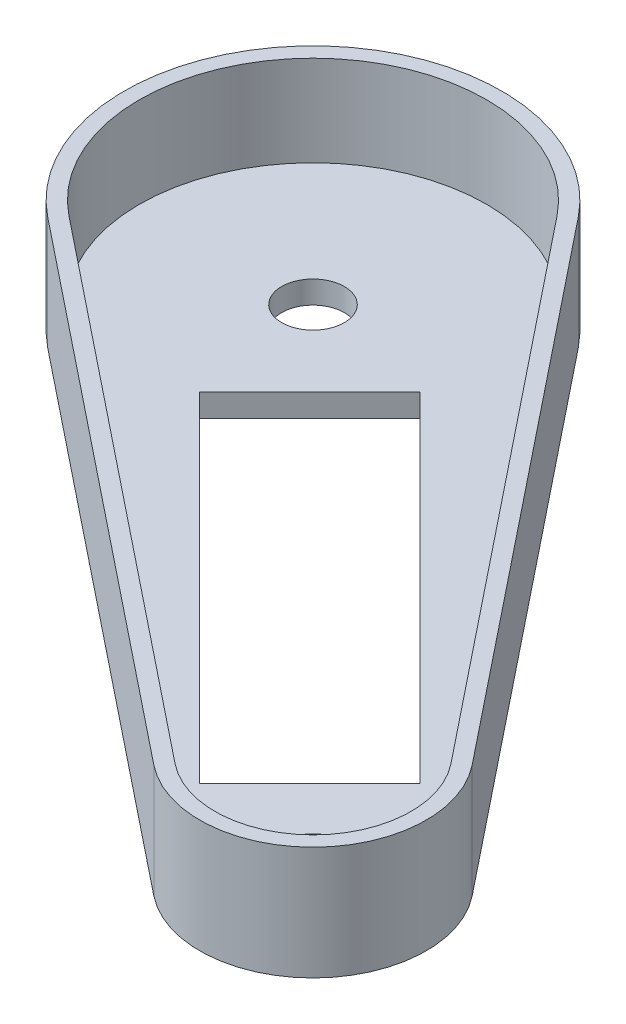
SolidWorks part; units mm, degrees
ref_plane "前视基准面" through (0, 0, 0) normal (0, 0, 1) x (1, 0, 0)
ref_plane "上视基准面" through (0, 0, 0) normal (0, 1, 0) x (1, 0, 0)
ref_plane "右视基准面" through (0, 0, 0) normal (1, 0, 0) x (0, 0, -1)
other "Configuration Table"
sketch "草图1" plane through (0, 0, 0) normal (0, 1, 0) x (1, 0, 0)
  line L0 (-1002.0771, 0) -> (49101.7763, 0) construction
  line L1 (0, -1002.0771) -> (0, 49101.7763) construction
  line L2 (0, 0) -> (63.6396, -63.6396)
  line L3 (19.5324, 15.604) -> (75.359, -54.2772)
  line L4 (-15.604, -19.5324) -> (54.2772, -75.359)
  circle A0 centre (0, 0) radius 4.15
  circle A1 centre (63.6396, -63.6396) radius 4.15
  circle A2 centre (63.6396, -63.6396) radius 15
  circle A3 centre (0, 0) radius 25
  dimension "D2" = 8.3
  dimension "D3" = 8.3
  dimension "D4" = 50
  dimension "D5" = 30
  dimension "D1" = 90
extrude "凸台-拉伸1" add sketch "草图1" along normal blind 3
sketch "草图3" plane through (0, 3, 0) normal (0, 1, 0) x (1, 0, 0)
  line L0 (19.5324, 15.604) -> (75.359, -54.2772)
  line L1 (19.5324, 15.604) -> (75.359, -54.2772) construction
  line L2 (-15.604, -19.5324) -> (54.2772, -75.359)
  line L3 (-14.3557, -17.9698) -> (55.5255, -73.7965)
  line L4 (17.9698, 14.3557) -> (73.7965, -55.5255)
  circle A0 centre (0, 0) radius 25
  circle A1 centre (63.6396, -63.6396) radius 15
  circle A2 centre (0, 0) radius 23
  circle A3 centre (63.6396, -63.6396) radius 13
  line M3 (-15.604, -19.5324) -> (54.2772, -75.359)
  arc M4 (54.2772, -75.359) -> (75.359, -54.2772) centre (63.6396, -63.6396) ccw
  line M5 (75.359, -54.2772) -> (19.5324, 15.604)
  arc M6 (19.5324, 15.604) -> (-15.604, -19.5324) centre (0, 0) ccw
  dimension "D1" = 2
  dimension "D2" = 2
extrude "凸台-拉伸2" add sketch "草图3" along normal blind 12 contours A1 L3 A0 M3 | A2 L4 A0 L3 M6 | A1 A0 L4 M5 | A3 L3 A1 L4 M4
sketch "草图4" plane through (0, 3, 0) normal (0, 1, 0) x (1, 0, 0)
  line L0 (0, 0) -> (63.6396, -63.6396)
  line L1 (10.0553, -10.0553) -> (2.5299, -17.5807)
  line L2 (2.5299, -17.5807) -> (47.3842, -62.435)
  line L3 (47.3842, -62.435) -> (54.9096, -54.9096)
  line L4 (54.9096, -54.9096) -> (61.988, -47.8313)
  line L5 (61.988, -47.8313) -> (17.1337, -2.977)
  line L6 (17.1337, -2.977) -> (10.0553, -10.0553)
extrude "切除-拉伸1" cut sketch "草图4" against normal through all contours L5 L6 L0 L4 | L2 L3 L0 L1
